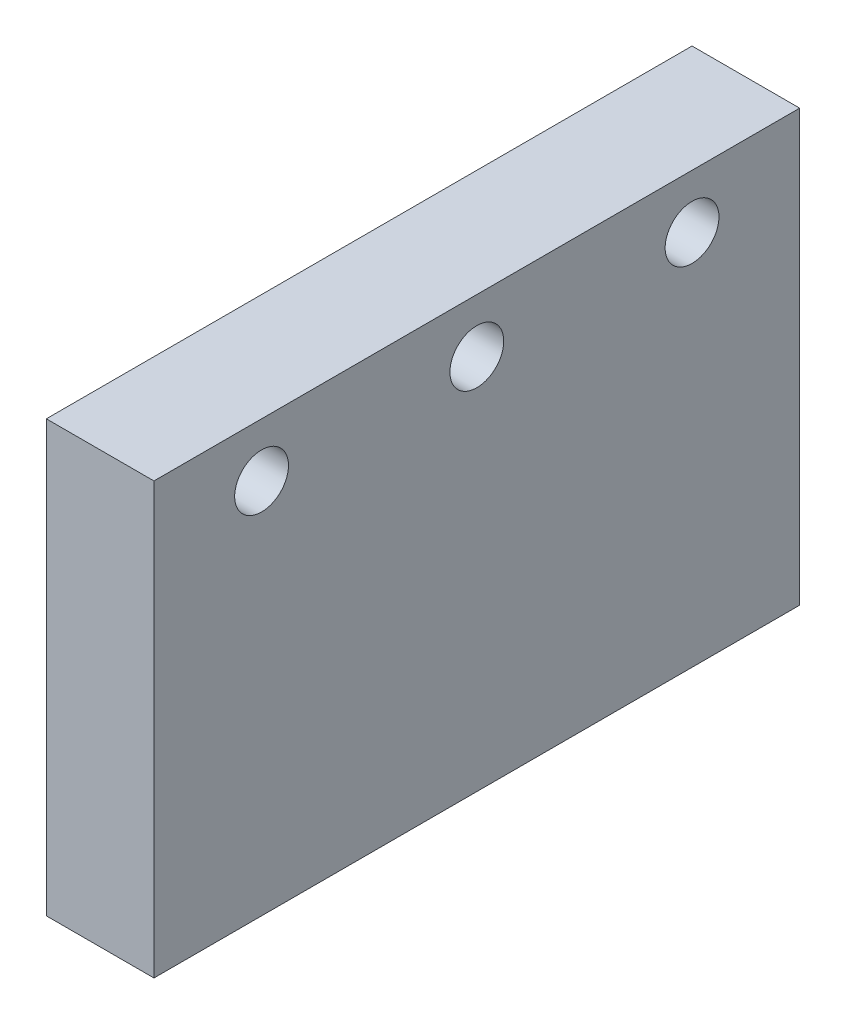
SolidWorks part; units mm, degrees
material "6061 Alloy"
ref_plane "Front" through (0, 0, 0) normal (0, 0, 1) x (1, 0, 0)
ref_plane "Top" through (0, 0, 0) normal (0, 1, 0) x (1, 0, 0)
ref_plane "Right" through (0, 0, 0) normal (1, 0, 0) x (0, 0, -1)
sketch "Sketch2" plane through (0, 0, 0) normal (0, 0, 1) x (1, 0, 0)
  line L7 (-6.35, 25.4) -> (6.35, 25.4)
  line L9 (6.35, -12.7) -> (6.35, -25.4)
  line L10 (6.35, 25.4) -> (6.35, -12.7)
  line L11 (-6.35, 25.4) -> (-6.35, 12.7)
  line L14 (-6.35, 12.7) -> (-6.35, -25.4)
  line L15 (-6.35, -25.4) -> (6.35, -25.4)
  dimension "D1" = 12.7
  dimension "D2" = 50.8
  dimension "D3" = 12.7
  dimension "D4" = 12.7
  dimension "D5" = 25.4
  dimension "D6" = 6.35
extrude "Boss-Extrude1" add sketch "Sketch2" along normal mid plane 76.2
hole_wizard "1/4\"-20 threaded hole" positions "Sketch7" profile "Sketch6" hole size "#97" standard "ANSI Inch" end condition through all
sketch "Sketch7" plane through (6.35, 0, 0) normal (1, 0, 0) x (0, 0, -1)
  line L0 (-38.1, 25.4) -> (38.1, 25.4) construction
  point P0 (-25.4, 19.05)
  point P2 (0, 19.05)
  point P4 (25.4, 19.05)
  dimension "D1" = 6.35
  dimension "D2" = 25.4
  dimension "D3" = 25.4
sketch "Sketch6" plane through (6.35, 19.05, 25.4) normal (0, 1, 0) x (0, 0, -1)
  line L0 (0, 0) -> (0, 12.7)
  line L1 (0, 12.7) -> (3.175, 12.7)
  line L2 (3.175, 12.7) -> (3.175, 0)
  line L5 (3.175, 0) -> (0, 0)
  line L11 (0, -6.35) -> (0, 107.95) construction
  dimension "Thru Hole Dia." = 6.35
  dimension "Thru Hole Depth" = 12.7
